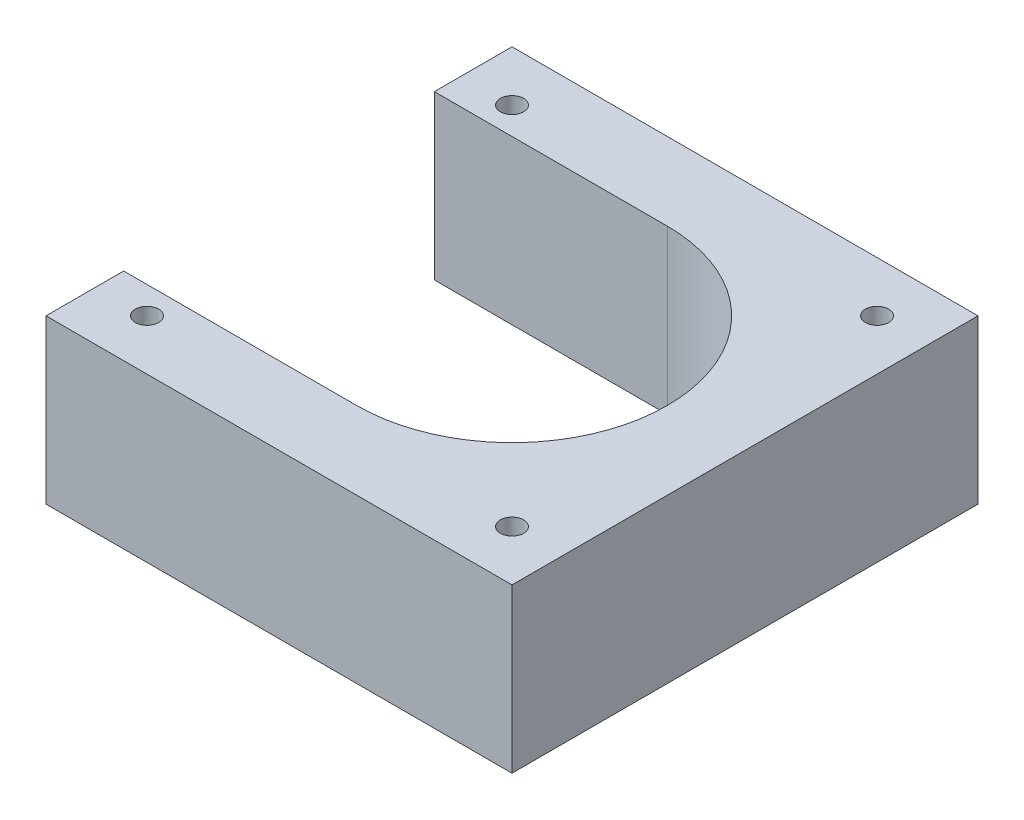
SolidWorks part; units mm, degrees
ref_plane "Front Plane" through (0, 0, 0) normal (0, 0, 1) x (1, 0, 0)
ref_plane "Top Plane" through (0, 0, 0) normal (0, 1, 0) x (1, 0, 0)
ref_plane "Right Plane" through (0, 0, 0) normal (1, 0, 0) x (0, 0, -1)
sketch "Sketch1" plane through (0, 0, 0) normal (0, 1, 0) x (1, 0, 0)
  line L0 (0, 20) -> (-30, 20)
  line L1 (-30, 30) -> (30, 30)
  line L2 (-30, 30) -> (-30, 20)
  line L3 (-30, -30) -> (30, -30)
  line L4 (30, 30) -> (30, -30)
  line L5 (-30, 30) -> (30, -30) construction
  line L6 (-30, -30) -> (30, 30) construction
  line L7 (0, -20) -> (-30, -20)
  line L8 (-30, -20) -> (-30, -30)
  circle A0 centre (-23.5, 23.5) radius 1.5
  circle A1 centre (23.5, 23.5) radius 1.5
  circle A2 centre (-23.5, -23.5) radius 1.5
  circle A3 centre (23.5, -23.5) radius 1.5
  arc A4 (0, -20) -> (0, 20) centre (0, 0) ccw
  point P0 (0, 0)
  dimension "D3" = 3
  dimension "D8" = 40
  dimension "D1" = 60
  dimension "D2" = 60
  dimension "D4" = 47
  dimension "D5" = 47
  dimension "D6" = 23.5
  dimension "D7" = 23.5
extrude "Boss-Extrude1" add sketch "Sketch1" along normal blind 21
